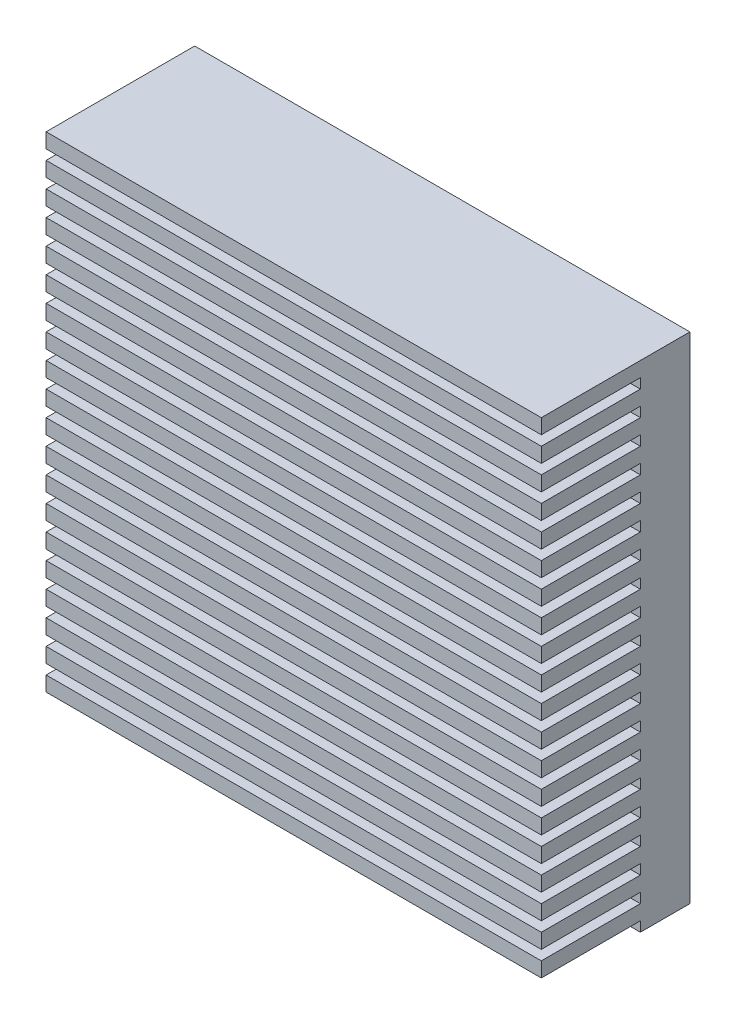
SolidWorks part; units mm, degrees
ref_plane "Front Plane" through (0, 0, 0) normal (0, 0, 1) x (1, 0, 0)
ref_plane "Top Plane" through (0, 0, 0) normal (0, 1, 0) x (1, 0, 0)
ref_plane "Right Plane" through (0, 0, 0) normal (1, 0, 0) x (0, 0, -1)
sketch "Sketch1" plane through (0, 0, 0) normal (0, 0, 1) x (1, 0, 0)
  line L1 (-25, -25) -> (25, -25)
  line L2 (-25, -25) -> (-25, 25)
  line L3 (-25, 25) -> (25, 25)
  line L4 (25, -25) -> (25, 25)
  line L5 (-25, -25) -> (25, 25) construction
  line L6 (-25, 25) -> (25, -25) construction
  point P0 (0, 0)
  dimension "D1" = 50
  dimension "D2" = 50
extrude "Boss-Extrude1" add sketch "Sketch1" along normal blind 5
sketch "Sketch2" plane through (0, 0, 5) normal (0, 0, 1) x (1, 0, 0)
  line L0 (25, -25) -> (25, 25) construction
  line L1 (-25, 25) -> (25, 25)
  line L2 (-25, 25) -> (-25, 23.5)
  line L3 (-25, 23.5) -> (25, 23.5)
  line L4 (25, 25) -> (25, 23.5)
  line L5 (-25, 22.5) -> (-25, 21)
  line L6 (-25, 21) -> (25, 21)
  line L7 (-25, 22.5) -> (25, 22.5)
  line L8 (25, 22.5) -> (25, 21)
  line L9 (-25, 20) -> (-25, 18.5)
  line L10 (-25, 18.5) -> (25, 18.5)
  line L11 (-25, 20) -> (25, 20)
  line L12 (25, 20) -> (25, 18.5)
  line L13 (-25, 17.5) -> (-25, 16)
  line L14 (-25, 16) -> (25, 16)
  line L15 (-25, 17.5) -> (25, 17.5)
  line L16 (25, 17.5) -> (25, 16)
  line L17 (-25, 15) -> (-25, 13.5)
  line L18 (-25, 13.5) -> (25, 13.5)
  line L19 (-25, 15) -> (25, 15)
  line L20 (25, 15) -> (25, 13.5)
  line L21 (-25, 12.5) -> (-25, 11)
  line L22 (-25, 11) -> (25, 11)
  line L23 (-25, 12.5) -> (25, 12.5)
  line L24 (25, 12.5) -> (25, 11)
  line L25 (-25, 10) -> (-25, 8.5)
  line L26 (-25, 8.5) -> (25, 8.5)
  line L27 (-25, 10) -> (25, 10)
  line L28 (25, 10) -> (25, 8.5)
  line L29 (-25, 7.5) -> (-25, 6)
  line L30 (-25, 6) -> (25, 6)
  line L31 (-25, 7.5) -> (25, 7.5)
  line L32 (25, 7.5) -> (25, 6)
  line L33 (-25, 5) -> (-25, 3.5)
  line L34 (-25, 3.5) -> (25, 3.5)
  line L35 (-25, 5) -> (25, 5)
  line L36 (25, 5) -> (25, 3.5)
  line L37 (-25, 2.5) -> (-25, 1)
  line L38 (-25, 1) -> (25, 1)
  line L39 (-25, 2.5) -> (25, 2.5)
  line L40 (25, 2.5) -> (25, 1)
  line L41 (-25, 0) -> (-25, -1.5)
  line L42 (-25, -1.5) -> (25, -1.5)
  line L43 (-25, 0) -> (25, 0)
  line L44 (25, 0) -> (25, -1.5)
  line L45 (-25, -2.5) -> (-25, -4)
  line L46 (-25, -4) -> (25, -4)
  line L47 (-25, -2.5) -> (25, -2.5)
  line L48 (25, -2.5) -> (25, -4)
  line L49 (-25, -5) -> (-25, -6.5)
  line L50 (-25, -6.5) -> (25, -6.5)
  line L51 (-25, -5) -> (25, -5)
  line L52 (25, -5) -> (25, -6.5)
  line L53 (-25, -7.5) -> (-25, -9)
  line L54 (-25, -9) -> (25, -9)
  line L55 (-25, -7.5) -> (25, -7.5)
  line L56 (25, -7.5) -> (25, -9)
  line L57 (-25, -10) -> (-25, -11.5)
  line L58 (-25, -11.5) -> (25, -11.5)
  line L59 (-25, -10) -> (25, -10)
  line L60 (25, -10) -> (25, -11.5)
  line L61 (-25, -12.5) -> (-25, -14)
  line L62 (-25, -14) -> (25, -14)
  line L63 (-25, -12.5) -> (25, -12.5)
  line L64 (25, -12.5) -> (25, -14)
  line L65 (-25, -15) -> (-25, -16.5)
  line L66 (-25, -16.5) -> (25, -16.5)
  line L67 (-25, -15) -> (25, -15)
  line L68 (25, -15) -> (25, -16.5)
  line L69 (-25, -17.5) -> (-25, -19)
  line L70 (-25, -19) -> (25, -19)
  line L71 (-25, -17.5) -> (25, -17.5)
  line L72 (25, -17.5) -> (25, -19)
  line L73 (-25, -20) -> (-25, -21.5)
  line L74 (-25, -21.5) -> (25, -21.5)
  line L75 (-25, -20) -> (25, -20)
  line L76 (25, -20) -> (25, -21.5)
  line L77 (-25, -22.5) -> (-25, -24)
  line L78 (-25, -24) -> (25, -24)
  line L79 (-25, -22.5) -> (25, -22.5)
  line L80 (25, -22.5) -> (25, -24)
  dimension "D1" = 1.5
  dimension "D2" = 20
extrude "Boss-Extrude2" add sketch "Sketch2" along normal blind 10
